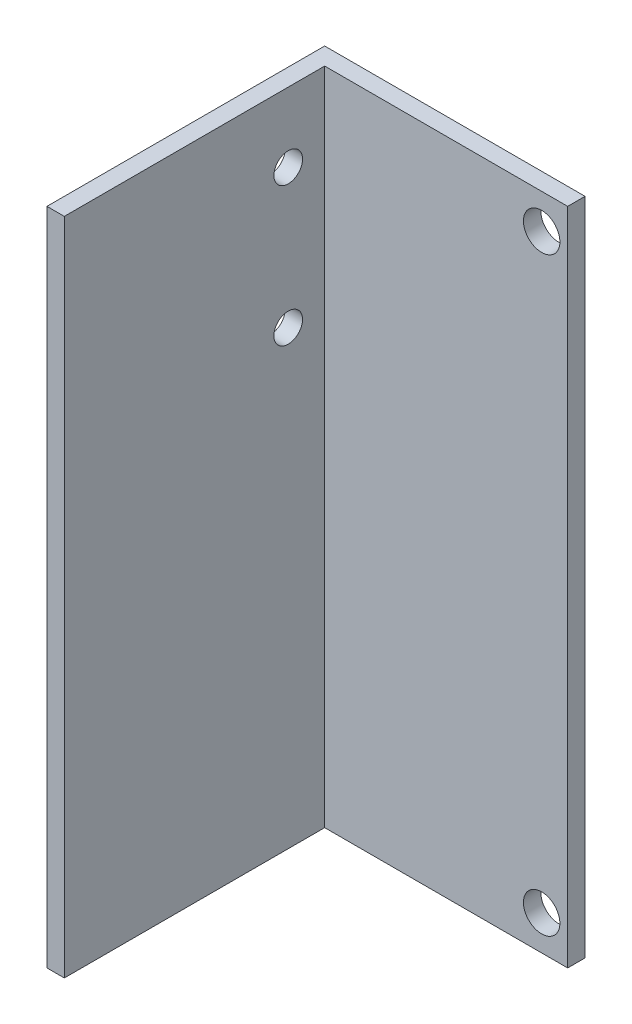
SolidWorks part; units mm, degrees
ref_plane "正面" through (0, 0, 0) normal (0, 0, 1) x (1, 0, 0)
ref_plane "平面" through (0, 0, 0) normal (0, 1, 0) x (1, 0, 0)
ref_plane "右側面" through (0, 0, 0) normal (1, 0, 0) x (0, 0, -1)
sketch "ｽｹｯﾁ1" plane through (0, 0, 0) normal (0, 0, 1) x (1, 0, 0)
  line L1 (0, 0) -> (30, 0)
  line L2 (0, 0) -> (0, -76)
  line L3 (0, -76) -> (30, -76)
  line L4 (30, 0) -> (30, -76)
  dimension "D1" = 30
  dimension "D2" = 76
extrude "押し出し1" add sketch "ｽｹｯﾁ1" along normal blind 2
sketch "ｽｹｯﾁ2" plane through (0, 0, 2) normal (0, 0, 1) x (1, 0, 0)
  line L0 (0, -76) -> (30, -76) construction
  line L1 (0, 0) -> (2, 0)
  line L2 (0, 0) -> (0, -76)
  line L3 (0, -76) -> (2, -76)
  line L4 (2, 0) -> (2, -76)
  dimension "D1" = 2
extrude "押し出し2" add sketch "ｽｹｯﾁ2" along normal blind 30
sketch "ｽｹｯﾁ3" plane through (0, 0, 0) normal (0, 0, -1) x (-1, 0, 0)
  line L0 (-27, 0) -> (-27, -76) construction
  line L1 (-30, 0) -> (0, 0) construction
  line L2 (0, -76) -> (-30, -76) construction
  line L3 (0, 0) -> (0, -76) construction
  circle A0 centre (-27, -4) radius 2.1
  circle A1 centre (-27, -72) radius 2.1
  dimension "D2" = 4.2
  dimension "D3" = 4.2
  dimension "D4" = 68
  dimension "D1" = 27
  dimension "D5" = 4
extrude "押し出し3" cut sketch "ｽｹｯﾁ3" against normal through all
sketch "ｽｹｯﾁ4" plane through (0, 0, 0) normal (-1, 0, 0) x (0, 0, 1)
  circle A0 centre (6.2, -8) radius 1.65
  circle A1 centre (6.2, -24) radius 1.65
  point P0 (6.2, -8)
  point P1 (6.2, -24)
  dimension "D1" = 3.3
  dimension "D2" = 3.3
extrude "押し出し4" cut sketch "ｽｹｯﾁ4" against normal through all
